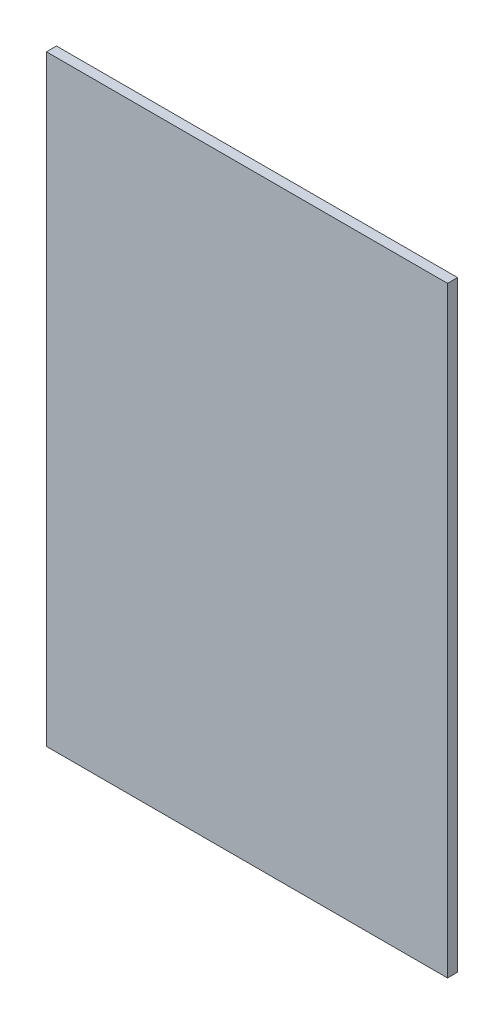
SolidWorks part; units mm, degrees
ref_plane "Plan de face" through (0, 0, 0) normal (0, 0, 1) x (1, 0, 0)
ref_plane "Plan de dessus" through (0, 0, 0) normal (0, 1, 0) x (1, 0, 0)
ref_plane "Plan de droite" through (0, 0, 0) normal (1, 0, 0) x (0, 0, -1)
sketch "Esquisse1" plane through (0, 0, 0) normal (0, 0, 1) x (1, 0, 0)
  line L1 (0, 209.7902) -> (200, 209.7902)
  line L2 (0, 209.7902) -> (0, -90.2098)
  line L3 (0, -90.2098) -> (200, -90.2098)
  line L4 (200, 209.7902) -> (200, -90.2098)
  dimension "D1" = 200
  dimension "D2" = 300
extrude "Boss.-Extru.1" add sketch "Esquisse1" along normal blind 5
